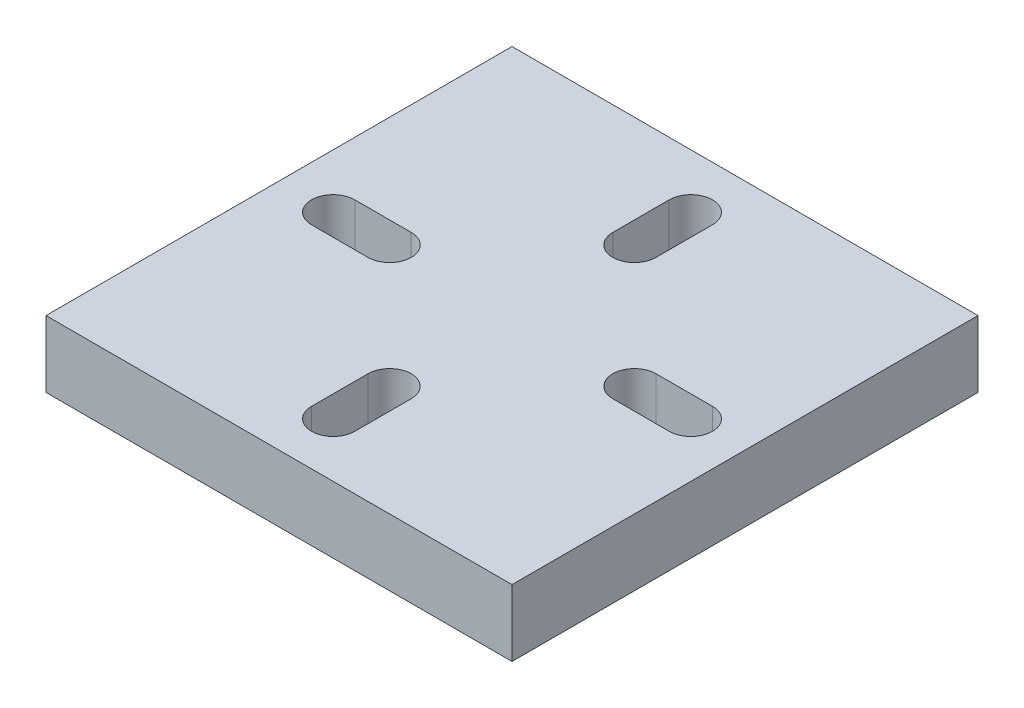
SolidWorks part; units mm, degrees
ref_plane "Front Plane" through (0, 0, 0) normal (0, 0, 1) x (1, 0, 0)
ref_plane "Top Plane" through (0, 0, 0) normal (0, 1, 0) x (1, 0, 0)
ref_plane "Right Plane" through (0, 0, 0) normal (1, 0, 0) x (0, 0, -1)
sketch "Sketch1" plane through (0, 0, 0) normal (0, 1, 0) x (1, 0, 0)
  line L1 (35, 35) -> (-35, 35)
  line L2 (35, 35) -> (35, -35)
  line L3 (35, -35) -> (-35, -35)
  line L4 (-35, 35) -> (-35, -35)
  line L5 (35, 35) -> (-35, -35) construction
  line L6 (35, -35) -> (-35, 35) construction
  point P0 (0, 0)
  dimension "D1" = 70
  dimension "D2" = 70
extrude "Boss-Extrude1" add sketch "Sketch1" along normal blind 10 contours L1 L4 L3 L2
sketch "Sketch2" plane through (0, 10, 0) normal (0, 1, 0) x (1, 0, 0)
  point P0 (55, 55)
  point P1 (55, -55)
  point P2 (-55, -55)
  point P3 (-55, 55)
  point P4 (0, 0)
  dimension "D1" = 110
  dimension "D2" = 55
  dimension "D3" = 55
  dimension "D4" = 55
sketch "Sketch4" plane through (0, 10, 0) normal (0, 1, 0) x (1, 0, 0)
  line L0 (-26.8701, 0) -> (-18.3848, 0) construction
  line L1 (-26.8701, 3.25) -> (-18.3848, 3.25)
  line L2 (-26.8701, -3.25) -> (-18.3848, -3.25)
  line L3 (0, 26.8701) -> (0, 18.3848) construction
  line L4 (3.25, 26.8701) -> (3.25, 18.3848)
  line L5 (-3.25, 26.8701) -> (-3.25, 18.3848)
  line L6 (26.8701, 0) -> (18.3848, 0) construction
  line L7 (26.8701, -3.25) -> (18.3848, -3.25)
  line L8 (26.8701, 3.25) -> (18.3848, 3.25)
  line L9 (0, -26.8701) -> (0, -18.3848) construction
  line L10 (-3.25, -26.8701) -> (-3.25, -18.3848)
  line L11 (3.25, -26.8701) -> (3.25, -18.3848)
  line L12 (-18.3848, 0) -> (-36.5755, 0) construction
  arc A0 (-26.8701, 3.25) -> (-26.8701, -3.25) centre (-26.8701, 0) ccw
  arc A1 (-18.3848, -3.25) -> (-18.3848, 3.25) centre (-18.3848, 0) ccw
  arc A2 (3.25, 26.8701) -> (-3.25, 26.8701) centre (0, 26.8701) ccw
  arc A3 (-3.25, 18.3848) -> (3.25, 18.3848) centre (0, 18.3848) ccw
  arc A4 (26.8701, -3.25) -> (26.8701, 3.25) centre (26.8701, 0) ccw
  arc A5 (18.3848, 3.25) -> (18.3848, -3.25) centre (18.3848, 0) ccw
  arc A6 (-3.25, -26.8701) -> (3.25, -26.8701) centre (0, -26.8701) ccw
  arc A7 (3.25, -18.3848) -> (-3.25, -18.3848) centre (0, -18.3848) ccw
  point P2 (-22.6274, 0)
  point P13 (0, 22.6274)
  point P20 (22.6274, 0)
  point P27 (0, -22.6274)
  point P32 (0, 0)
  dimension "D2" = 3.25
  dimension "D1" = 26.8701
  dimension "D3" = 18.3848
  dimension "D4" = 4
extrude "Cut-Extrude1" cut sketch "Sketch4" against normal through all
equation "\"D3@Sketch2\"=\"D1@Sketch2\"/2"
equation "\"D2@Sketch2\"=\"D1@Sketch2\"/2"
equation "\"D4@Sketch2\"=\"D3@Sketch2\""
